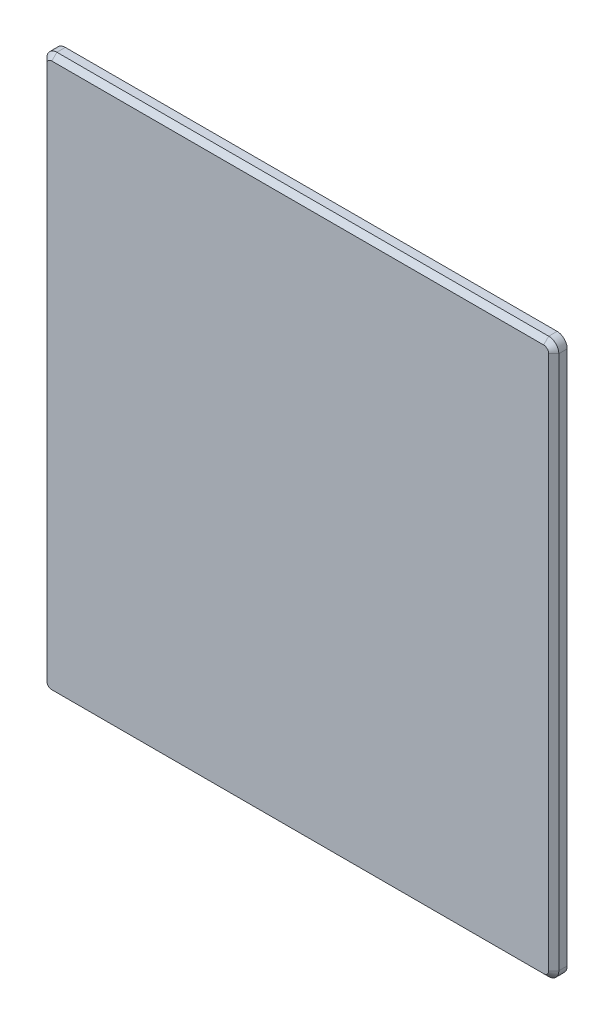
SolidWorks part; units mm, degrees
ref_plane "Plano frontal" through (0, 0, 0) normal (0, 0, 1) x (1, 0, 0)
ref_plane "Plano superior" through (0, 0, 0) normal (0, 1, 0) x (1, 0, 0)
ref_plane "Plano direito" through (0, 0, 0) normal (1, 0, 0) x (0, 0, -1)
sketch "Esboço1" plane through (0, 0, 0) normal (0, 0, 1) x (1, 0, 0)
  line L1 (-76, -82.32) -> (76, -82.32)
  line L2 (-76, -82.32) -> (-76, 82.32)
  line L3 (-76, 82.32) -> (76, 82.32)
  line L4 (76, -82.32) -> (76, 82.32)
  line L5 (-76, -82.32) -> (76, 82.32) construction
  line L6 (-76, 82.32) -> (76, -82.32) construction
  point P0 (0, 0)
  dimension "D1" = 152
  dimension "D2" = 164.64
extrude "Ressalto-extrusão1" add sketch "Esboço1" along normal blind 4
fillet "Filete1" radius 3 4 edges at (-76, 82.32, 2) (-76, -82.32, 2) (76, -82.32, 2) (76, 82.32, 2)
sketch "Esboço2" plane through (0, 0, 0) normal (0, 0, -1) x (-1, 0, 0)
  line L0 (-73, 82.32) -> (73, 82.32) construction
  line L1 (-71.5, -73.32) -> (71.5, -73.32)
  line L2 (-71.5, -73.32) -> (-71.5, -40.35)
  line L3 (-71.5, 77.82) -> (71.5, 77.82)
  line L4 (71.5, -73.32) -> (71.5, -40.35)
  line L5 (-71.5, -73.32) -> (71.5, 77.82) construction
  line L6 (-71.5, 77.82) -> (71.5, -73.32) construction
  line L7 (71.5, -35.35) -> (71.5, -21.68)
  line L8 (76, 79.32) -> (76, -79.32) construction
  line L9 (0, 77.82) -> (0, -73.32) construction
  line L10 (71.5, 56.32) -> (71.5, 77.82)
  line L11 (71.5, 56.32) -> (45, 56.32)
  line L13 (71.5, -21.68) -> (45, -21.68)
  line L14 (45, 56.32) -> (45, -21.68)
  line L15 (-71.5, -21.68) -> (-45, -21.68)
  line L16 (-45, 56.32) -> (-45, -21.68)
  line L17 (-71.5, 56.32) -> (-45, 56.32)
  line L18 (-71.5, 56.32) -> (-71.5, 77.82)
  line L19 (-71.5, -35.35) -> (-61, -35.35)
  line L20 (71.5, -35.35) -> (61, -35.35)
  line L22 (71.5, -40.35) -> (61, -40.35)
  line L23 (61, -35.35) -> (61, -40.35)
  line L24 (-61, -35.35) -> (-61, -40.35)
  line L25 (-71.5, -40.35) -> (-61, -40.35)
  line L26 (-71.5, -35.35) -> (-71.5, -21.68)
  point P0 (0, 2.25)
  dimension "D1" = 4.5
  dimension "D2" = 151.14
  dimension "D3" = 143
  dimension "D4" = 4.5
  dimension "D5" = 26.5
  dimension "D6" = 78
  dimension "D7" = 21.5
  dimension "D8" = 10.5
  dimension "D9" = 5
  dimension "D10" = 18.67
extrude "Ressalto-extrusão2" add sketch "Esboço2" along normal blind 4
fillet "Filete2" radius 3 8 edges at (45, 56.32, -2) (45, -21.68, -2) (-45, -21.68, -2) (-45, 56.32, -2) (71.5, 77.82, -2) (-71.5, 77.82, -2) (-71.5, -73.32, -2) (71.5, -73.32, -2)
fillet "Filete3" radius 1 10 edges at (-71.5, -40.35, -2) (71.5, -40.35, -2) (-61, -35.35, -2) (-71.5, -35.35, -2) (-71.5, -21.68, -2) (-71.5, 56.32, -2) (71.5, 56.32, -2) (71.5, -21.68, -2) (71.5, -35.35, -2) (61, -35.35, -2)
chamfer "Chanfro1" distance 1.5 angle 45 8 edges at (75.1213, 81.4413, 4) (76, 0, 4) (75.1213, -81.4413, 4) (0, -82.32, 4) (-75.1213, -81.4413, 4) (-76, 0, 4) (-75.1213, 81.4413, 4) (0, 82.32, 4)
chamfer "Chanfro2" distance 1 angle 45 38 edges at (-70.6213, -72.4413, -4) (0, -73.32, -4) (70.6213, -72.4413, -4) (71.5, -55.835, -4) (71.2071, -40.6429, -4) (65.75, -40.35, -4) (61, -38.35, -4) (61.2929, -35.6429, -4) (66.25, -35.35, -4) (71.2071, -35.0571, -4) (71.5, -28.515, -4) (71.2071, -21.9729, -4) (59.25, -21.68, -4) (45.8787, -20.8013, -4) (45, 17.32, -4) (45.8787, 55.4413, -4) (59.25, 56.32, -4) (71.2071, 56.6129, -4) (71.5, 66.07, -4) (70.6213, 76.9413, -4) (0, 77.82, -4) (-70.6213, 76.9413, -4) (-71.5, 66.07, -4) (-71.2071, 56.6129, -4) (-59.25, 56.32, -4) (-45.8787, 55.4413, -4) (-45, 17.32, -4) (-45.8787, -20.8013, -4) (-59.25, -21.68, -4) (-71.2071, -21.9729, -4) (-71.5, -28.515, -4) (-71.2071, -35.0571, -4) (-66.25, -35.35, -4) (-61.2929, -35.6429, -4) (-61, -38.35, -4) (-65.75, -40.35, -4) (-71.2071, -40.6429, -4) (-71.5, -55.835, -4)
sketch "Esboço3" plane through (0, 0, 0) normal (0, 0, -1) x (-1, 0, 0)
  line L0 (-68, 48.32) -> (-68, -11.68) construction
  line L4 (68, 48.32) -> (68, -11.68) construction
  line L5 (-48, 56.32) -> (-70.5, 56.32) construction
  line L6 (0, 0) -> (0, 82.32) construction
  line L7 (-73, 82.32) -> (73, 82.32) construction
  line L8 (-45, -18.68) -> (-45, 53.32) construction
  circle A0 centre (-68, 48.32) radius 2.1
  circle A1 centre (-68, -11.68) radius 2.1
  circle A4 centre (-68, 18.32) radius 2.1
  circle A6 centre (68, 18.32) radius 2.1
  circle A7 centre (68, -11.68) radius 2.1
  circle A8 centre (68, 48.32) radius 2.1
  dimension "D1" = 4.2
  dimension "D2" = 60
  dimension "D3" = 8
  dimension "D4" = 23
extrude "Corte-extrusão1" cut sketch "Esboço3" against normal blind 1
